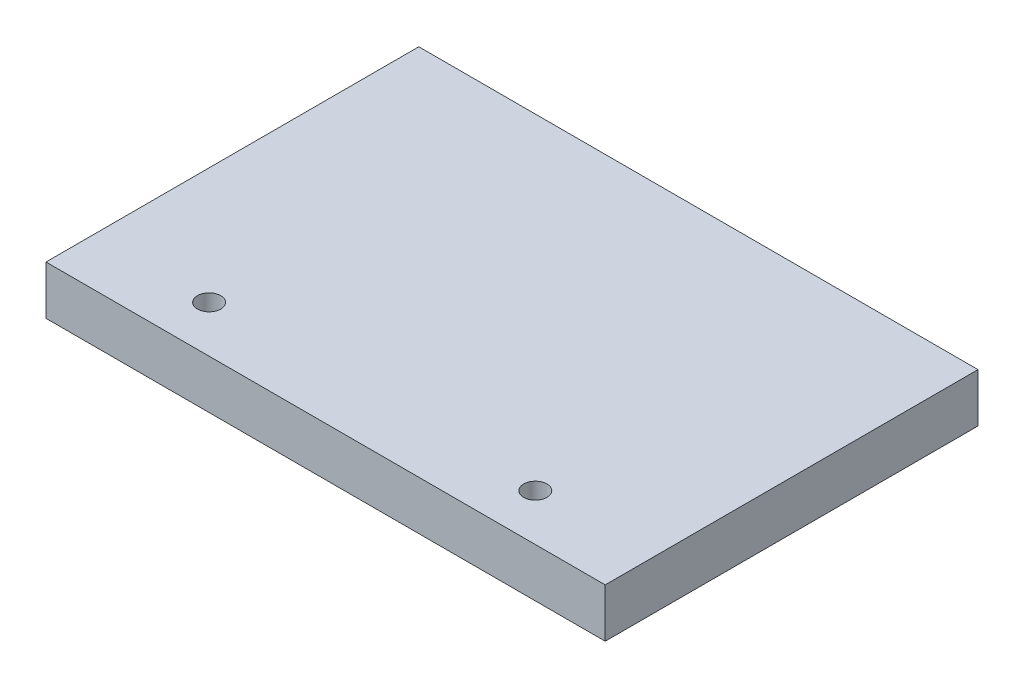
SolidWorks part; units mm, degrees
ref_plane "Front Plane" through (0, 0, 0) normal (0, 0, 1) x (1, 0, 0)
ref_plane "Top Plane" through (0, 0, 0) normal (0, 1, 0) x (1, 0, 0)
ref_plane "Right Plane" through (0, 0, 0) normal (1, 0, 0) x (0, 0, -1)
sketch "Sketch1" plane through (0, 0, 0) normal (0, 1, 0) x (1, 0, 0)
  line L1 (0, 0) -> (76.2, 0)
  line L2 (0, 0) -> (0, 50.8)
  line L3 (0, 50.8) -> (76.2, 50.8)
  line L4 (76.2, 0) -> (76.2, 50.8)
  dimension "D1" = 76.2
  dimension "D2" = 50.8
extrude "Boss-Extrude1" add sketch "Sketch1" along normal blind 6.6548
sketch "Sketch2" plane through (0, 6.6548, 0) normal (0, 1, 0) x (1, 0, 0)
  line L0 (15.875, 6.35) -> (60.325, 6.35) construction
  line L1 (38.1, 6.35) -> (38.1, 0) construction
  line L2 (0, 0) -> (76.2, 0) construction
  line L3 (38.1, 6.35) -> (38.1, 50.8) construction
  line L4 (76.2, 50.8) -> (0, 50.8) construction
  line L6 (60.325, 6.35) -> (76.2, 6.35) construction
  line L7 (76.2, 0) -> (76.2, 50.8) construction
  circle A0 centre (15.875, 6.35) radius 1.5875
  circle A1 centre (60.325, 6.35) radius 1.5875
  dimension "D2" = 3.175
  dimension "D1" = 44.45
  dimension "D3" = 6.35
extrude "Cut-Extrude1" cut sketch "Sketch2" against normal through all
